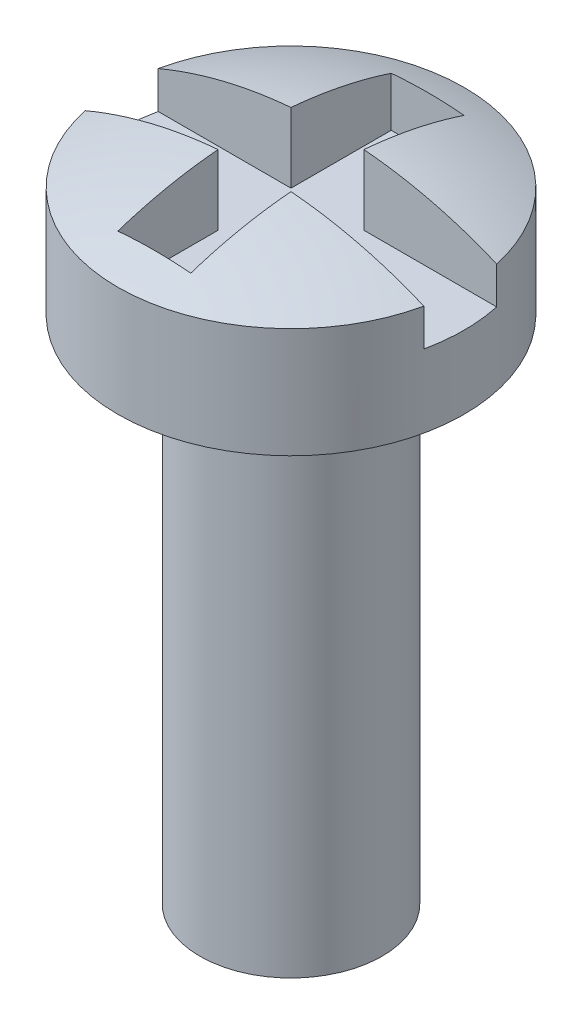
SolidWorks part; units mm, degrees
ref_plane "前视基准面" through (0, 0, 0) normal (0, 0, 1) x (1, 0, 0)
ref_plane "上视基准面" through (0, 0, 0) normal (0, 1, 0) x (1, 0, 0)
ref_plane "右视基准面" through (0, 0, 0) normal (1, 0, 0) x (0, 0, -1)
sketch "草图1" plane through (0, 0, 0) normal (0, 1, 0) x (1, 0, 0)
  circle A0 centre (0, 0) radius 1.25
  dimension "D1" = 2.5
extrude "拉伸1" add sketch "草图1" along normal blind 7
sketch "草图2" plane through (0, 7, 0) normal (0, 1, 0) x (-1, 0, 0)
  circle A0 centre (0, 0) radius 2.375
  dimension "D1" = 4.75
extrude "拉伸2" add sketch "草图2" along normal blind 2
sketch "草图3" plane through (0, 9, 0) normal (0, 1, 0) x (-1, 0, 0)
  line L0 (4.0624, 0) -> (-4.2778, 0) construction
  line L1 (0, -3.5166) -> (0, 3.738) construction
  line L3 (3.5023, -0.5) -> (-3.5023, -0.5)
  line L4 (3.5023, -0.5) -> (3.5023, 0.5)
  line L5 (3.5023, 0.5) -> (-3.5023, 0.5)
  line L6 (-3.5023, -0.5) -> (-3.5023, 0.5)
  dimension "D1" = 1
extrude "切除-拉伸1" cut sketch "草图3" against normal blind 1
sketch "草图4" plane through (0, 9, 0) normal (0, 1, 0) x (-1, 0, 0)
  line L0 (0, -3.8639) -> (0, 3.6765) construction
  line L1 (1.7727, 0) -> (-1.7019, 0) construction
  line L2 (0.5, -1.875) -> (-0.5, -1.875)
  line L3 (0.5, -1.875) -> (0.5, 1.875)
  line L4 (0.5, 1.875) -> (-0.5, 1.875)
  line L5 (-0.5, -1.875) -> (-0.5, 1.875)
  dimension "D1" = 1
  dimension "D2" = 3.75
extrude "切除-拉伸2" cut sketch "草图4" against normal blind 1
sketch "草图5" plane through (0, 0, 0) normal (1, 0, 0) x (0, 0, -1)
  line L0 (0, -2.1059) -> (0, 12.2815) construction
  line L1 (-0.5, 9) -> (-2.375, 9) construction
  line L2 (0, 10.9998) -> (-4.5494, 10.9998)
  line L3 (-4.5494, 6.9119) -> (-4.5494, 10.9998)
  line L5 (0, 10.9998) -> (0, 9)
  arc A2 (0, 9) -> (-4.5494, 6.9119) centre (0, 3) ccw
  point P9 (0, 0)
  point P10 (0, 0)
  dimension "D1" = 6
revolve "切除-旋转16" cut sketch "草图5" angle 360 about L0
